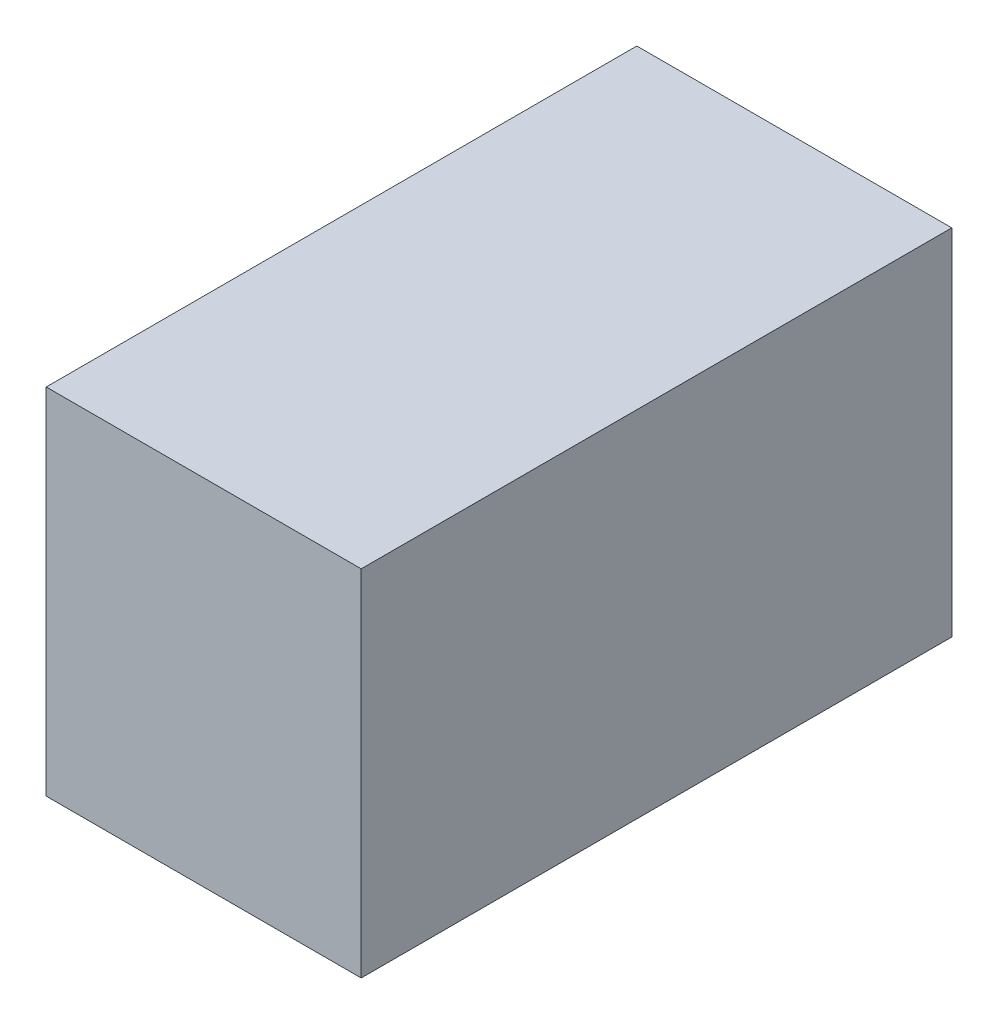
SolidWorks part; units mm, degrees
material "Chrome Stainless Steel"
ref_plane "Front Plane" through (0, 0, 0) normal (0, 0, 1) x (1, 0, 0)
ref_plane "Top Plane" through (0, 0, 0) normal (0, 1, 0) x (1, 0, 0)
ref_plane "Right Plane" through (0, 0, 0) normal (1, 0, 0) x (0, 0, -1)
sketch "Sketch1" plane through (0, 0, 0) normal (0, 0, 1) x (1, 0, 0)
  line L1 (0, 0) -> (101.6, 0)
  line L2 (0, 0) -> (0, 114.3)
  line L3 (0, 114.3) -> (101.6, 114.3)
  line L4 (101.6, 0) -> (101.6, 114.3)
  dimension "D1" = 101.6
  dimension "D2" = 114.3
extrude "Boss-Extrude1" add sketch "Sketch1" along normal blind 190.5
